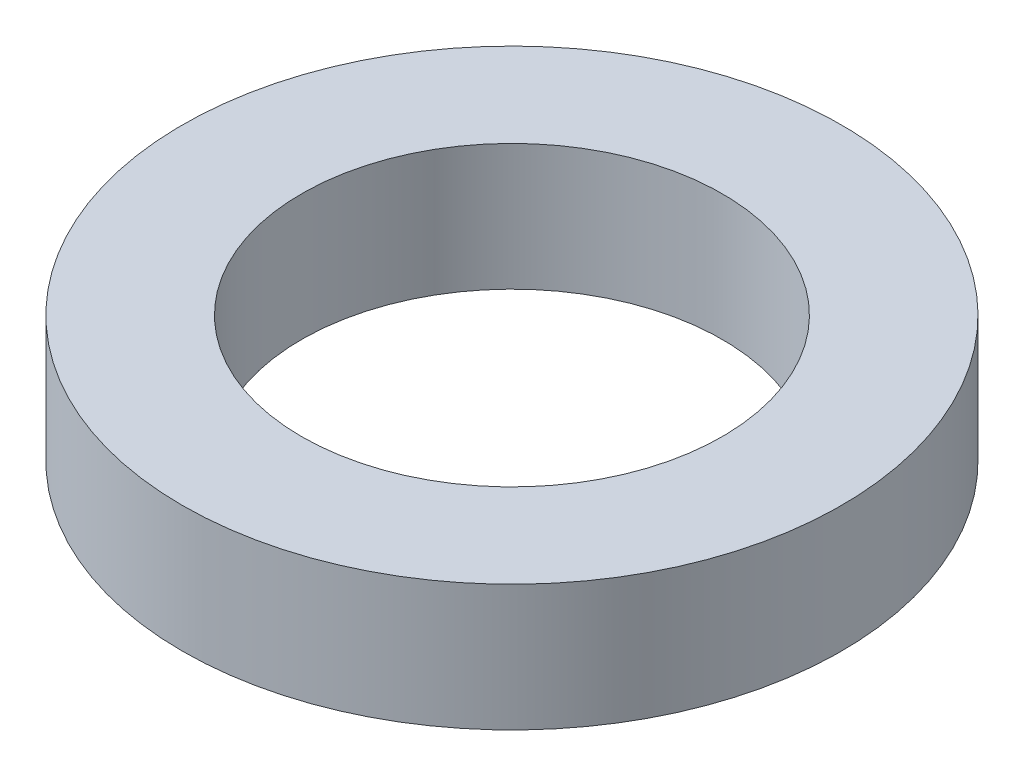
SolidWorks part; units mm, degrees
ref_plane "前视基准面" through (0, 0, 0) normal (0, 0, 1) x (1, 0, 0)
ref_plane "上视基准面" through (0, 0, 0) normal (0, 1, 0) x (1, 0, 0)
ref_plane "右视基准面" through (0, 0, 0) normal (1, 0, 0) x (0, 0, -1)
other "Configuration Table"
sketch "草图1" plane through (0, 0, 0) normal (0, 1, 0) x (1, 0, 0)
  circle A0 centre (0, 0) radius 15
  circle A1 centre (0, 0) radius 23.5
  dimension "D1" = 47
  dimension "D2" = 30
extrude "凸台-拉伸1" add sketch "草图1" along normal blind 9
